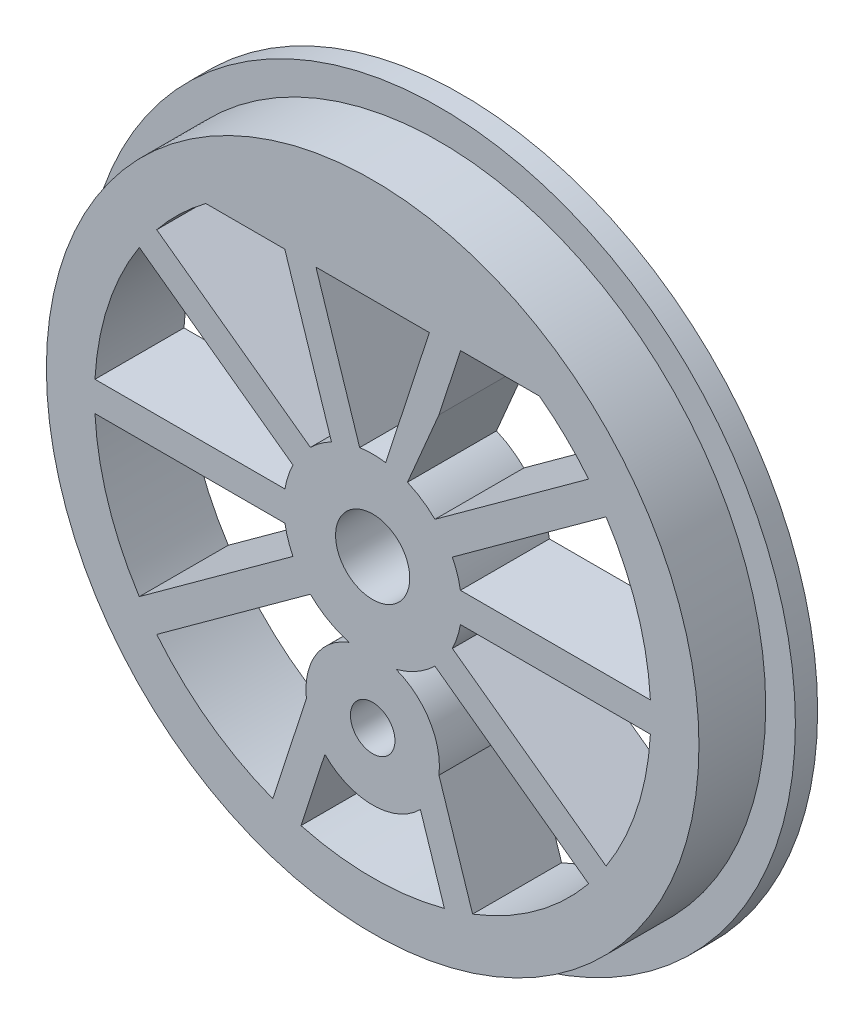
SolidWorks part; units mm, degrees
ref_plane "Plan de face" through (0, 0, 0) normal (0, 0, 1) x (1, 0, 0)
ref_plane "Plan de dessus" through (0, 0, 0) normal (0, 1, 0) x (1, 0, 0)
ref_plane "Plan de droite" through (0, 0, 0) normal (1, 0, 0) x (0, 0, -1)
sketch "Esquisse1" plane through (0, 0, 0) normal (0, 0, 1) x (1, 0, 0)
  line L0 (0, 0) -> (0, -10) construction
  line L1 (5.374, -2.6684) -> (18.3678, -12.1089)
  line L2 (3.2193, -13.1442) -> (5.8403, -21.2106)
  line L3 (0, 0) -> (0, 27.2327) construction
  line L4 (4.4698, -10.5205) -> (7.7424, -20.5926)
  line L5 (5.9161, 1) -> (21.9773, 1)
  line L6 (-21.9773, 1) -> (-21.9773, -1) construction
  line L8 (-21.9773, -1) -> (21.7985, -1) construction
  line L10 (0, 0) -> (0, -25.2075) construction
  line L11 (-5.374, -2.6684) -> (-18.3678, -12.1089)
  line L12 (-11.25, 15) -> (11.25, 15)
  line L13 (-18.75, 0) -> (18.75, 0) construction
  line L14 (-4.1984, -4.2864) -> (-17.1922, -13.7269)
  line L15 (5.374, 2.6684) -> (18.3678, 12.1089)
  line L16 (5.9161, -1) -> (21.9773, -1)
  line L17 (-5.9161, -1) -> (-21.9773, -1)
  line L18 (-5.8403, -21.2106) -> (-3.2193, -13.1442)
  line L19 (-7.7424, -20.5926) -> (-4.4698, -10.5205)
  line L20 (-21.9773, 1) -> (-5.9161, 1)
  line L21 (4.1984, 4.2864) -> (17.1922, 13.7269)
  line L22 (4.4698, 10.5205) -> (7.7424, 20.5926)
  line L23 (3.2193, 13.1442) -> (5.8403, 21.2106)
  line L24 (4.1984, -4.2864) -> (17.1922, -13.7269)
  line L25 (-5.8403, 21.2106) -> (-3.2193, 13.1442)
  line L26 (-7.7424, 20.5926) -> (-4.4698, 10.5205)
  line L27 (-4.1984, 4.2864) -> (-17.1922, 13.7269)
  line L28 (-5.374, 2.6684) -> (-18.3678, 12.1089)
  line L29 (-4.4698, 10.5205) -> (-2.7792, 5.3175)
  line L30 (-3.2193, 13.1442) -> (-0.8771, 5.9355)
  line L31 (4.4698, 10.5205) -> (2.3462, 5.5223)
  line L32 (3.2193, 13.1442) -> (0.8771, 5.9355)
  circle A0 centre (0, 0) radius 6
  circle A1 centre (0, 0) radius 2.5
  arc A3 (1.5827, -5.7875) -> (-1.5827, -5.7875) centre (0, -10) cw
  circle A4 centre (0, -10) radius 1.5
  circle A5 centre (0, 0) radius 22
  circle A6 centre (0, 0) radius 18.75
  circle A7 centre (0, 0) radius 19.5
  point P4 (0, -10)
  point P13 (0, 0)
  point P24 (0, 0)
  point P38 (0, 15)
  point P44 (0, 0)
  point P47 (0, 0)
  dimension "D1" = 12
  dimension "D2" = 5
  dimension "D4" = 4.5
  dimension "D5" = 3
  dimension "D6" = 44
  dimension "D9" = 37.5
  dimension "D22" = 39
  dimension "D23" = 15
  dimension "D3" = 10
  dimension "D8" = 2
  dimension "D10" = 8.4816
  dimension "D11" = 1
  dimension "D7" = 16.0612
  dimension "D12" = 16.0612
  dimension "D13" = 36
  dimension "D14" = 108
  dimension "D15" = 1
  dimension "D16" = 2
  dimension "D17" = 2
  dimension "D18" = 36
  dimension "D19" = 8.4816
  dimension "D20" = 1
  dimension "D21" = 2
extrude "Boss.-Extru.1" add sketch "Esquisse1" along normal blind 6 contours A0 A1 | A3 A0 A4 | L2 A6 L4 A3 | L19 A6 L18 A3 | L11 A6 L14 A0 | L20 A6 L17 A0 | L27 A6 L28 A0 | A0 L30 L25 L12 L26 L29 | A0 L31 L22 L12 L23 L32 | L15 A6 L21 A0 | L16 A6 L5 A0 | L24 A6 L1 A0 | A7 L14 A5 L19 | A7 L11 A5 L14 | A7 L17 A5 L11 | A7 L20 A5 L17 | A7 L28 A5 L20 | A7 L27 A5 L28 | A7 L26 A5 L27 | A7 L25 A5 L26 | L26 A6 L12 | L26 A7 L27 A6 | L27 A7 L28 A6 | L25 A7 L26 A6 | L25 A6 L26 L12 | L23 A6 L25 L12 | L23 A7 L25 A6 | L22 A6 L23 L12 | L22 A7 L23 A6 | L21 A7 L22 A6 | L12 A6 L22 | A7 L21 A5 L22 | A7 L22 A5 L23 | A7 L15 A5 L21 | A7 L5 A5 L15 | A7 L23 A5 L25 | A7 L16 A5 L5 | L16 A7 L5 A6 | L5 A7 L15 A6 | L15 A7 L21 A6 | A7 L1 A5 L16 | L1 A7 L16 A6 | A7 L24 A5 L1 | L24 A7 L1 A6 | A7 L4 A5 L24 | L4 A7 L24 A6 | A7 L2 A5 L4 | L2 A7 L4 A6 | L18 A7 L2 A6 | A7 L18 A5 L2 | L19 A7 L18 A6 | L14 A7 L19 A6 | L11 A7 L14 A6 | L28 A7 L20 A6 | L20 A7 L17 A6 | L17 A7 L11 A6 | A7 L19 A5 L18
sketch "Esquisse4" plane through (0, 0, 0) normal (0, 0, -1) x (-1, 0, 0)
  circle A0 centre (0, 0) radius 24
  circle A1 centre (0, 0) radius 22
  dimension "D1" = 48
  dimension "D2" = 44
extrude "Boss.-Extru.3" add sketch "Esquisse4" against normal blind 1.5 contours A0 | A1
